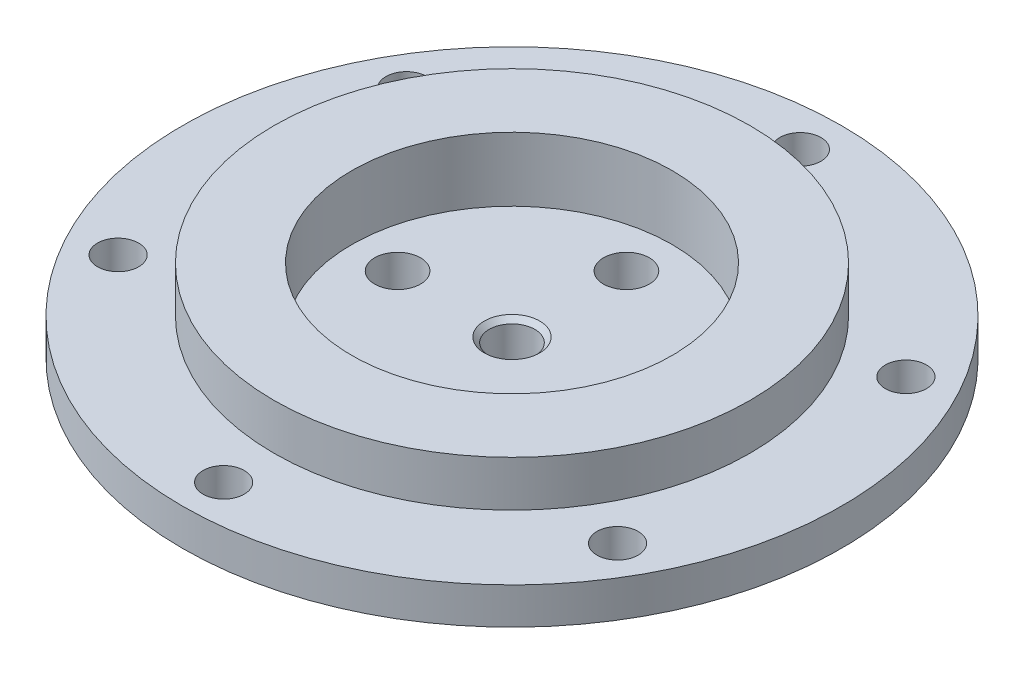
SolidWorks part; units mm, degrees
ref_plane "Front Plane" through (0, 0, 0) normal (0, 0, 1) x (1, 0, 0)
ref_plane "Top Plane" through (0, 0, 0) normal (0, 1, 0) x (1, 0, 0)
ref_plane "Right Plane" through (0, 0, 0) normal (1, 0, 0) x (0, 0, -1)
sketch "Sketch1" plane through (0, 0, 0) normal (0, 0, 1) x (1, 0, 0)
  line L0 (0, 0) -> (0, 60.5882) construction
  line L1 (27.5, 0) -> (27.5, -4)
  line L2 (27.5, -4) -> (0, -4)
  line L3 (0, -4) -> (0, 2)
  line L4 (26, 4) -> (36, 4)
  line L5 (36, 4) -> (36, 0)
  line L6 (36, 0) -> (27.5, 0)
  line L7 (0, 0) -> (27.5, 0) construction
  line L8 (26, 4) -> (26, 9)
  line L18 (26, 9) -> (17.5, 9)
  line L19 (17.5, 9) -> (17.5, 2)
  line L20 (17.5, 2) -> (0, 2)
  dimension "D1" = 72
  dimension "D2" = 4
  dimension "D3" = 4
  dimension "D4" = 55
  dimension "D5" = 52
  dimension "D6" = 5
  dimension "D11" = 35
  dimension "7" = 7
revolve "Revolve1" add sketch "Sketch1" angle 360 about L0
sketch "Sketch2" plane through (0, 4, 0) normal (0, 1, 0) x (1, 0, 0)
  circle A0 centre (0, 0) radius 31.5 construction
  circle A1 centre (0, 31.5) radius 2.25
  circle A2 centre (27.2798, 15.75) radius 2.25
  circle A3 centre (27.2798, -15.75) radius 2.25
  circle A4 centre (0, -31.5) radius 2.25
  circle A5 centre (-27.2798, -15.75) radius 2.25
  circle A6 centre (-27.2798, 15.75) radius 2.25
  point P17 (0, 0)
  dimension "D1" = 63
  dimension "D2" = 4.5
  dimension "D3" = 6
extrude "Cut-Extrude1" cut sketch "Sketch2" against normal through all
sketch "Sketch3" plane through (0, 4, 0) normal (0, 1, 0) x (1, 0, 0)
  circle A0 centre (0, 31.5) radius 5
  circle A1 centre (27.2798, 15.75) radius 5
  circle A2 centre (27.2798, -15.75) radius 5
  circle A3 centre (0, -31.5) radius 5
  circle A4 centre (-27.2798, -15.75) radius 5
  circle A5 centre (-27.2798, 15.75) radius 5
  point P16 (0, 0)
  dimension "D1" = 10
  dimension "D2" = 6
extrude "Cut-Extrude2" [suppressed] cut sketch "Sketch3" against normal blind 10
sketch "Sketch4" plane through (0, 2, 0) normal (0, 1, 0) x (1, 0, 0)
  circle A0 centre (0, 0) radius 12.5 construction
  circle A1 centre (12.5, 0) radius 2.5
  circle A2 centre (0, -12.5) radius 2.5
  circle A3 centre (-12.5, 0) radius 2.5
  circle A4 centre (0, 12.5) radius 2.5
  point P14 (0, 0)
  dimension "D1" = 25
  dimension "D2" = 5
  dimension "D3" = 4
extrude "Cut-Extrude3" cut sketch "Sketch4" against normal blind 10
hole_wizard "M6 Tapped Hole1" positions "3DSketch2" profile "Sketch5" tap size "M6" standard "ISO"
sketch3d "3DSketch2"
  line L0 (-12.5, -4, 0) -> (-12.5, 2, 0) construction
  line L1 (12.5, -4, 0) -> (12.5, 2, 0) construction
  line L2 (0, -4, -12.5) -> (0, 2, -12.5) construction
  line L3 (0, -4, 12.5) -> (0, 2, 12.5) construction
  point P0 (-12.5, 9, 0)
  point P4 (12.5, 9, 0)
  point P8 (0, 9, -12.5)
  point P12 (0, 9, 12.5)
sketch "Sketch5" plane through (-12.5, 9, 0) normal (1, 0, 0) x (0, 0, 1)
  line L0 (0, 0) -> (0, 16.5022)
  line L1 (0, 16.5022) -> (2.5, 15)
  line L2 (2.5, 15) -> (2.5, 0.525)
  line L3 (2.5, 0.525) -> (3.025, 0)
  line L5 (3.025, 0) -> (0, 0)
  line L6 (-2.5, 0.525) -> (-3.025, 0) construction
  line L10 (0, 16.5022) -> (-2.5, 15) construction
  line L11 (0, -6.35) -> (0, 107.95) construction
  dimension "Tap Drill Dia." = 5
  dimension "Tap Drill Depth" = 15
  dimension "Near C'Sink Dia." = 6.05
  dimension "Near C'Sink Angle" = 90
  dimension "Drill Angle" = 118
sketch "Sketch9" plane through (0, 2, 0) normal (0, 1, 0) x (1, 0, 0)
  circle A0 centre (0, 0) radius 2.5
  dimension "D1" = 5
extrude "Cut-Extrude4" cut sketch "Sketch9" against normal through all
hole_wizard "M6 Tapped Hole2" positions "3DSketch4" profile "Sketch10" tap size "M6" standard "ISO"
sketch3d "3DSketch4"
  line L0 (0, -4, 0) -> (0, 2, 0) construction
  point P0 (0, 2, 0)
sketch "Sketch10" plane through (0, 2, 0) normal (1, 0, 0) x (0, 0, 1)
  line L0 (0, 0) -> (0, 66.5022)
  line L1 (0, 66.5022) -> (2.5, 65)
  line L2 (2.5, 65) -> (2.5, 0.525)
  line L3 (2.5, 0.525) -> (3.025, 0)
  line L5 (3.025, 0) -> (0, 0)
  line L6 (-2.5, 0.525) -> (-3.025, 0) construction
  line L10 (0, 66.5022) -> (-2.5, 65) construction
  line L11 (0, -6.35) -> (0, 107.95) construction
  dimension "Tap Drill Dia." = 5
  dimension "Tap Drill Depth" = 65
  dimension "Near C'Sink Dia." = 6.05
  dimension "Near C'Sink Angle" = 90
  dimension "Drill Angle" = 118
cosmetic thread "Hole Thread1" parameters "D1"=62, "D2"=7.05
